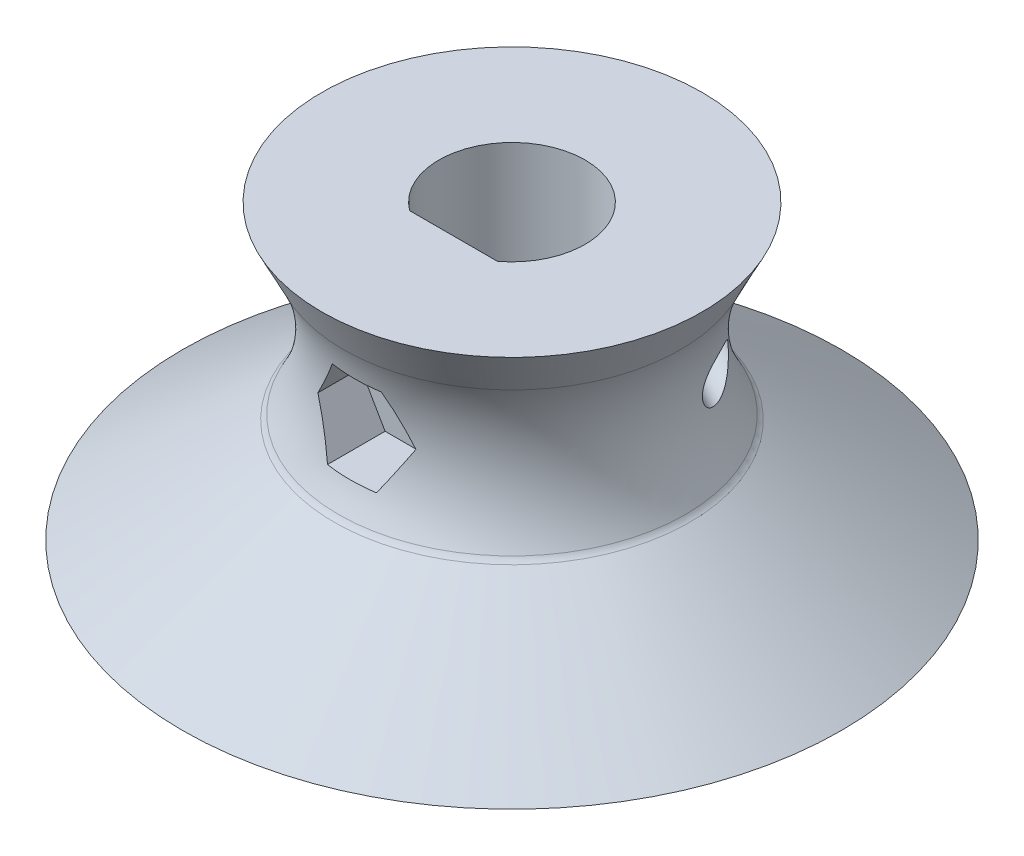
SolidWorks part; units mm, degrees
ref_plane "前视基准面" through (0, 0, 0) normal (0, 0, 1) x (1, 0, 0)
ref_plane "上视基准面" through (0, 0, 0) normal (0, 1, 0) x (1, 0, 0)
ref_plane "右视基准面" through (0, 0, 0) normal (1, 0, 0) x (0, 0, -1)
sketch "草图1" plane through (0, 0, 0) normal (0, 1, 0) x (1, 0, 0)
  line L0 (-3, -4) -> (3, -4)
  circle A0 centre (0, 0) radius 8
  circle A1 centre (0, 0) radius 5
  dimension "D1" = 16
  dimension "D2" = 10
  dimension "D3" = 4
extrude "凸台-拉伸1" add sketch "草图1" along normal blind 16 contours A0 A1 | L0 A1
sketch "草图2" plane through (0, 0, 0) normal (0, 0, 1) x (1, 0, 0)
  line L0 (0, 19.268) -> (0, -4.9986) construction
  line L1 (8, 16) -> (13, 16)
  line L2 (8, 8) -> (10, 8) construction
  line L3 (8, 0) -> (8, 16) construction
  line L4 (13, 16) -> (9, 8)
  line L5 (14, 0) -> (9, 8)
  line L6 (8, 0) -> (14, 0)
  line L7 (8, 16) -> (8, 0)
  dimension "D1" = 1
  dimension "D2" = 5
  dimension "D3" = 6
revolve "旋转1" add sketch "草图2" angle 360 about L0
fillet "圆角1" radius 10 1 edges at (0, 8, 9)
sketch "草图3" plane through (0, 0, 0) normal (0, 0, 1) x (1, 0, 0)
  line L0 (0, 16) -> (0, 0) construction
  line L1 (-14, 0) -> (14, 0) construction
  line L2 (-3, 16) -> (3, 16) construction
  circle A0 centre (0, 8) radius 1.65
  dimension "D1" = 3.3
extrude "切除-拉伸1" cut sketch "草图3" against normal through all both and the other way through all
ref_plane "基准面1" through (0, 0, 15) normal (0, 0, 1) x (1, 0, 0)
sketch "草图4" plane through (0, 0, 15) normal (0, 0, 1) x (1, 0, 0)
  line L0 (0, 16) -> (0, 0) construction
  line L1 (-3, 16) -> (3, 16) construction
  line L3 (3.3486, 8) -> (1.6743, 10.9)
  line L4 (1.6743, 10.9) -> (-1.6743, 10.9)
  line L5 (-1.6743, 10.9) -> (-3.3486, 8)
  line L6 (-3.3486, 8) -> (-1.6743, 5.1)
  line L7 (-1.6743, 5.1) -> (1.6743, 5.1)
  line L8 (1.6743, 5.1) -> (3.3486, 8)
  circle A1 centre (0, 8) radius 2.9 construction
  dimension "D1" = 5.8
extrude "切除-拉伸2" cut sketch "草图4" against normal offset from surface (8 mm away) 3 up to face at (-1.65, 8, 4)
ref_plane "基准面2" through (0, 0, -15) normal (0, 0, 1) x (1, 0, 0)
sketch "草图6" plane through (0, 0, -15) normal (0, 0, 1) x (1, 0, 0)
  line L0 (0, 16) -> (0, 0) construction
  line L1 (5, 16) -> (-5, 16) construction
  circle A0 centre (0, 8) radius 3.25
  dimension "D1" = 6.5
extrude "切除-拉伸3" cut sketch "草图6" along normal offset from surface (7.5 mm away) 11.5 up to face at (-1.65, 8, 4)
sketch "草图7" plane through (0, 0, 0) normal (0, 0, 1) x (1, 0, 0)
  line L0 (0, 21.037) -> (0, -5.5034) construction
  line L1 (11.9724, 3.2441) -> (22.5364, -4)
  line L2 (22.5364, -4) -> (19, -4)
  line L3 (19, -4) -> (13.1669, 0)
  line L4 (-14, 0) -> (14, 0) construction
  line L5 (13.1669, 0) -> (11.9724, 3.2441)
  dimension "D1" = 4
  dimension "D2" = 2
  dimension "D3" = 19
revolve "旋转2" add sketch "草图7" angle 360 about L0
fillet "圆角2" radius 1 1 edges at (0, 3.2441, -11.9724)
ref_plane "基准面4" through (0, 8, 0) normal (0, 1, 0) x (1, 0, 0)
sketch "草图10" plane through (0, 8, 0) normal (0, 1, 0) x (1, 0, 0)
  line L0 (1.254, 8.9083) -> (14.3637, 2.1551) construction
  line L1 (1.254, 8.9083) -> (1.8265, 10.0195)
  line L2 (1.8265, 10.0195) -> (14.9362, 3.2664)
  line L3 (14.9362, 3.2664) -> (14.3637, 2.1551)
  line L4 (14.3637, 2.1551) -> (21.1891, -1.3608) construction
  line L5 (1.254, 8.9083) -> (14.3637, 2.1551)
  line L6 (1.254, 8.9083) -> (14.3637, 2.1551)
  dimension "D1" = 1.25
revolve "切除-旋转1" cut sketch "草图10" angle 360 about L4
ref_plane "基准面5" through (0, 8, 0) normal (0, -1, 0) x (-1, 0, 0)
sketch "草图11" plane through (0, 8, 0) normal (0, -1, 0) x (-1, 0, 0)
  line L1 (-3.3486, -7) -> (-1.6743, -7) construction
  line L2 (-3.3486, -7) -> (-1.6743, -7)
  line L3 (3, -4) -> (-3, -4) construction
  line L5 (3, -4) -> (1.6644, -4)
  arc A0 (3.0345, -10.0022) -> (3.2041, 9.9492) centre (0, 0) ccw construction
  arc A1 (3, -4) -> (-3, -4) centre (0, 0) ccw construction
  arc A2 (3, -4) -> (-3, -4) centre (0, 0) ccw
  arc A4 (3.0345, -10.0022) -> (3.2041, 9.9492) centre (0, 0) ccw
  dimension "D2" = 5
  dimension "D4" = 10.4524
  dimension "D1" = 3
  dimension "D3" = 4
